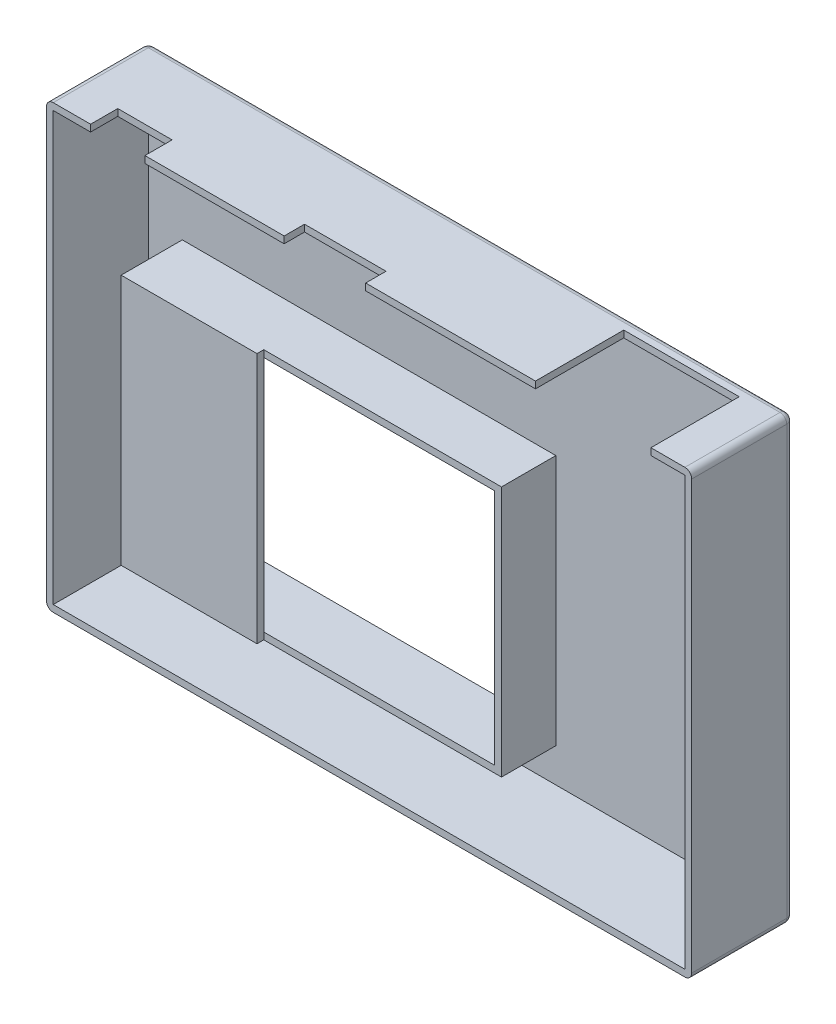
SolidWorks part; units mm, degrees
material "ABS"
ref_plane "Спереди" through (0, 0, 0) normal (0, 0, 1) x (1, 0, 0)
ref_plane "Сверху" through (0, 0, 0) normal (0, 1, 0) x (1, 0, 0)
ref_plane "Справа" through (0, 0, 0) normal (1, 0, 0) x (0, 0, -1)
sketch "Эскиз1" plane through (0, 0, 0) normal (0, 0, 1) x (1, 0, 0)
  line L1 (0, 0) -> (95, 0)
  line L2 (0, 0) -> (0, 65)
  line L3 (0, 65) -> (95, 65)
  line L4 (95, 0) -> (95, 65)
extrude "Болванка" add sketch "Эскиз1" along normal blind 15
sketch "Эскиз2" plane through (0, 0, 15) normal (0, 0, 1) x (1, 0, 0)
  line L1 (1, 1) -> (94, 1)
  line L2 (1, 1) -> (1, 64)
  line L3 (1, 64) -> (94, 64)
  line L4 (94, 1) -> (94, 64)
extrude "Внутр" cut sketch "Эскиз2" against normal blind 14
sketch "Эскиз3" plane through (0, 0, 15) normal (0, 0, 1) x (1, 0, 0)
  line L0 (95, 65) -> (0, 65) construction
  line L1 (72, 65) -> (89, 65)
  line L2 (72, 65) -> (72, 64)
  line L3 (72, 64) -> (89, 64)
  line L4 (89, 65) -> (89, 64)
  line L5 (94, 64) -> (1, 64) construction
extrude "Ethernet" cut sketch "Эскиз3" against normal blind 13
fillet "Скругление1" radius 1 1 edges at (47.5, 65, 0)
fillet "Скругление2" radius 1 3 edges at (0, 65, 8) (0, 64.7071, 0.2929) (0, 32, 0)
fillet "Скругление3" radius 1 3 edges at (0, 0, 8) (0.2929, 0, 0.2929) (48, 0, 0)
fillet "Скругление4" radius 1 5 edges at (95, 0, 8) (95, 0.2929, 0.2929) (95, 65, 8) (95, 64.7071, 0.2929) (95, 32.5, 0)
sketch "Эскиз4" plane through (0, 0, 15) normal (0, 0, 1) x (1, 0, 0)
  line L0 (72, 65) -> (1, 65) construction
  line L1 (6.5, 65) -> (14.5, 65)
  line L2 (6.5, 65) -> (6.5, 64)
  line L3 (6.5, 64) -> (14.5, 64)
  line L4 (14.5, 65) -> (14.5, 64)
  line L5 (94, 64) -> (1, 64) construction
extrude "USB" cut sketch "Эскиз4" against normal blind 4
sketch "Эскиз5" plane through (0, 0, 15) normal (0, 0, 1) x (1, 0, 0)
  line L0 (72, 65) -> (14.5, 65) construction
  line L1 (35, 65) -> (47, 65)
  line L2 (35, 65) -> (35, 64)
  line L3 (35, 64) -> (47, 64)
  line L4 (47, 65) -> (47, 64)
  line L5 (72, 64) -> (14.5, 64) construction
extrude "MicroSD" cut sketch "Эскиз5" against normal blind 3
sketch "Эскиз7" plane through (0, 0, 0) normal (0, 0, -1) x (-1, 0, 0)
  line L1 (-61, 6) -> (-6, 6)
  line L2 (-61, 6) -> (-61, 43)
  line L3 (-61, 43) -> (-6, 43)
  line L4 (-6, 6) -> (-6, 43)
extrude "Батарейный отсек" add sketch "Эскиз7" against normal blind 10
sketch "Эскиз6" plane through (0, 0, 0) normal (0, 0, -1) x (-1, 0, 0)
  line L1 (-7, 7) -> (-60, 7)
  line L2 (-7, 7) -> (-7, 42)
  line L3 (-7, 42) -> (-60, 42)
  line L4 (-60, 7) -> (-60, 42)
extrude "Под аккумулятор" cut sketch "Эскиз6" against normal blind 9
sketch "Эскиз8" plane through (0, 0, 10) normal (0, 0, 1) x (1, 0, 0)
  line L0 (6, 43) -> (61, 43) construction
  line L1 (61, 6) -> (26, 6)
  line L2 (61, 6) -> (61, 43)
  line L3 (61, 43) -> (26, 43)
  line L4 (26, 6) -> (26, 43)
extrude "Вытянуть8" cut sketch "Эскиз8" against normal blind 1
